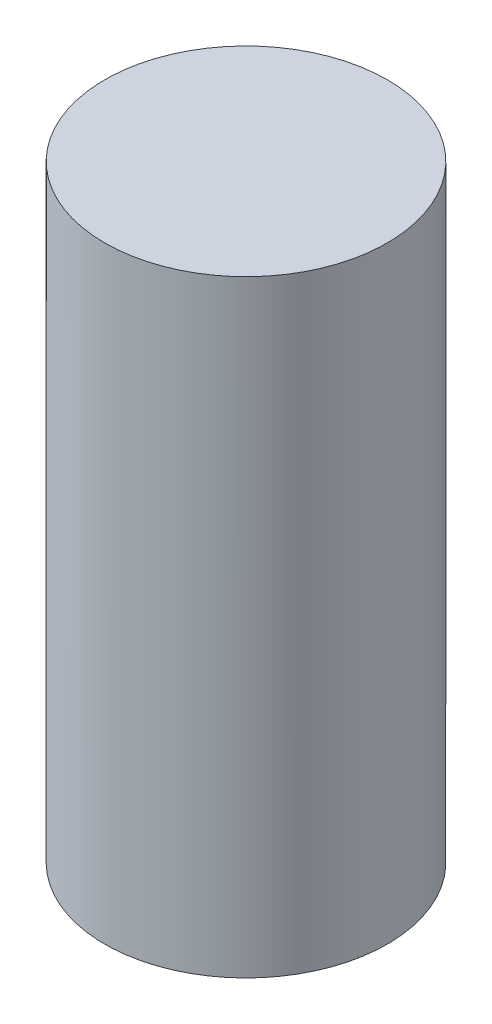
SolidWorks part; units mm, degrees
ref_plane "Plan de face" through (0, 0, 0) normal (0, 0, 1) x (1, 0, 0)
ref_plane "Plan de dessus" through (0, 0, 0) normal (0, 1, 0) x (1, 0, 0)
ref_plane "Plan de droite" through (0, 0, 0) normal (1, 0, 0) x (0, 0, -1)
sketch "Esquisse1" plane through (0, 0, 0) normal (0, 1, 0) x (1, 0, 0)
  circle A0 centre (0, 0) radius 73.61
  dimension "D1" = 147.22
extrude "Boss.-Extru.1" add sketch "Esquisse1" along normal blind 320
sketch "Sketch2" plane through (0, 0, 0) normal (0, 0, 1) x (1, 0, 0)
  line L0 (0, 187.9341) -> (0, -22.1687) construction
  line L1 (61.1208, 3.6166) -> (89.2937, 3.6166)
  line L2 (61.1208, 3.6166) -> (61.1208, -8.3211)
  line L3 (61.1208, -8.3211) -> (89.2937, -8.3211)
  line L4 (89.2937, 3.6166) -> (89.2937, -8.3211)
revolve "Cut-Revolve1" cut sketch "Sketch2" angle 360 about L0
